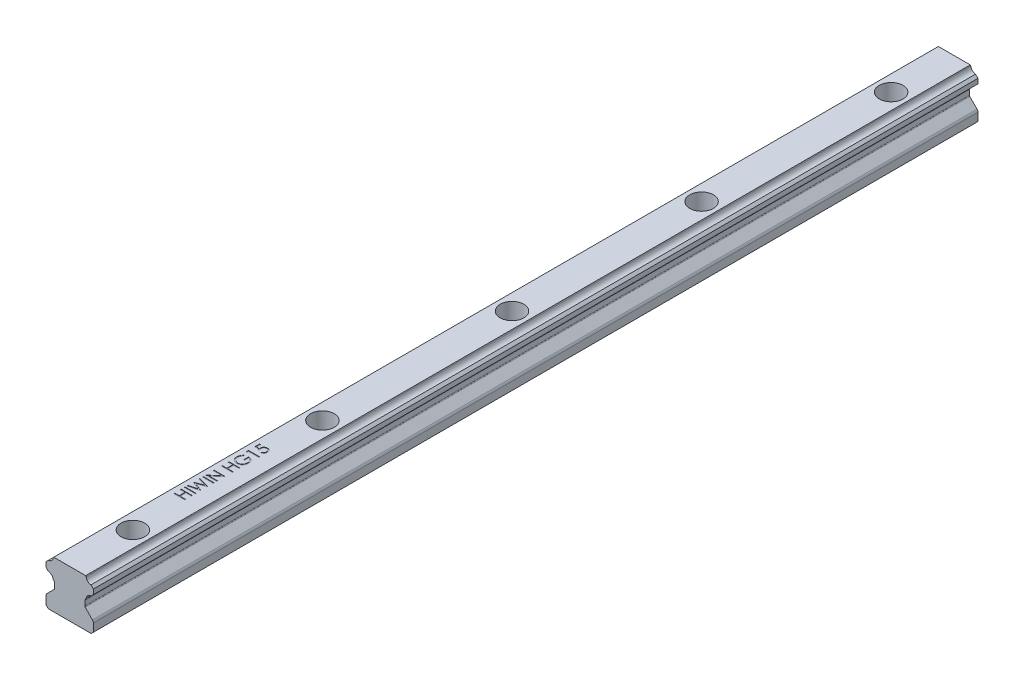
SolidWorks part; units mm, degrees
material "镀铬不锈钢"
ref_plane "前视基准面" through (0, 0, 0) normal (0, 0, 1) x (1, 0, 0)
ref_plane "上视基准面" through (0, 0, 0) normal (0, 1, 0) x (1, 0, 0)
ref_plane "右视基准面" through (0, 0, 0) normal (1, 0, 0) x (0, 0, -1)
sketch "草图1" plane through (0, 0, 0) normal (0, 0, 1) x (1, 0, 0)
  line L20 (7.5, 12.549) -> (6.7304, 13.3186)
  line L21 (-5.049, 15) -> (-5.1049, 14.9441)
  line L22 (-7.5, 12.549) -> (-7.5, 11.011)
  line L23 (6.7419, 10.2529) -> (7.5, 11.011)
  line L24 (-6.7304, 13.3186) -> (-7.5, 12.549)
  line L25 (-4.8872, 6.2704) -> (-7.2071, 3.9505)
  line L26 (-7.5, 0.7) -> (-6.8, 0)
  line L27 (7.2071, 3.9505) -> (4.8872, 6.2704)
  line L28 (-4.77, 8.1153) -> (-4.77, 6.5533)
  line L29 (7.5, 0.7) -> (7.5, 3.2434)
  line L30 (6.8, 0) -> (7.5, 0.7)
  line L31 (-6.8, 0) -> (6.8, 0)
  line L32 (-7.5, 3.2434) -> (-7.5, 0.7)
  line L33 (4.77, 6.5533) -> (4.77, 8.1153)
  line L34 (-5.1032, 8.6142) -> (-4.8872, 8.3982)
  line L35 (5.049, 15) -> (-5.049, 15)
  line L36 (5.1049, 14.9441) -> (5.049, 15)
  line L37 (7.5, 11.011) -> (7.5, 12.549)
  line L38 (4.8872, 8.3982) -> (5.1032, 8.6142)
  line L39 (-7.5, 11.011) -> (-6.7419, 10.2529)
  arc A14 (-5.217, 8.8451) -> (-5.1032, 8.6142) centre (-4.8204, 8.897) ccw
  arc A15 (5.1032, 8.6142) -> (5.217, 8.8451) centre (4.8204, 8.897) ccw
  arc A16 (-5.217, 8.8451) -> (-6.7419, 10.2529) centre (-6.8233, 8.6349) ccw
  arc A17 (-7.2071, 3.9505) -> (-7.5, 3.2434) centre (-6.5, 3.2434) ccw
  arc A18 (4.77, 6.5533) -> (4.8872, 6.2704) centre (5.17, 6.5533) ccw
  arc A19 (-5.1049, 14.9441) -> (-5.2183, 14.7157) centre (-4.822, 14.6613) ccw
  arc A20 (4.8872, 8.3982) -> (4.77, 8.1153) centre (5.17, 8.1153) ccw
  arc A21 (5.2183, 14.7157) -> (5.1049, 14.9441) centre (4.822, 14.6613) ccw
  arc A22 (-6.7304, 13.3186) -> (-5.2183, 14.7157) centre (-6.8233, 14.936) ccw
  arc A23 (6.7419, 10.2529) -> (5.217, 8.8451) centre (6.8233, 8.6349) ccw
  arc A24 (5.2183, 14.7157) -> (6.7304, 13.3186) centre (6.8233, 14.936) ccw
  arc A25 (7.5, 3.2434) -> (7.2071, 3.9505) centre (6.5, 3.2434) ccw
  arc A26 (-4.8872, 6.2704) -> (-4.77, 6.5533) centre (-5.17, 6.5533) ccw
  arc A27 (-4.77, 8.1153) -> (-4.8872, 8.3982) centre (-5.17, 8.1153) ccw
extrude "凸台-拉伸1" add sketch "草图1" against normal blind 280
hole_wizard "M4 六角凹头螺钉的柱形沉头孔1" positions "草图3" profile "草图2" counterbore size "M4" standard "ISO" end condition through all
sketch "草图3" plane through (0.2915, 15, -3.4663) normal (0, 1, 0) x (-1, 0, 0)
  point P0 (0.2915, -16.5337)
  dimension "D1" = 20
sketch "草图2" plane through (0, 15, -20) normal (1, 0, 0) x (0, 0, 1)
  line L0 (0, 0) -> (0, 15)
  line L1 (0, 15) -> (2.25, 15)
  line L3 (2.25, 15) -> (2.25, 5.3)
  line L4 (2.25, 5.3) -> (3.75, 5.3)
  line L5 (3.75, 5.3) -> (3.75, 0)
  line L7 (3.75, 0) -> (0, 0)
  line L11 (0, -6.35) -> (0, 107.95) construction
  dimension "通孔孔直径" = 4.5
  dimension "通孔孔深度" = 15
  dimension "柱形沉头孔直径" = 7.5
  dimension "柱形沉头孔深度" = 5.3
pattern_linear "阵列(线性)1" count 5 spacing 60 along (0, 0, -1) of "M4 六角凹头螺钉的柱形沉头孔1"
sketch "草图6" plane through (0, 15, 0) normal (0, 1, 0) x (1, 0, 0)
  line L0 (0, 20) -> (0, 80) construction
  text T0 "HIWIN HG15"
extrude "切除-拉伸1" cut sketch "草图6" against normal blind 0.1
equation "\"D1@凸台-拉伸1\" = 2 * \"D1@草图3\" + \"D3@阵列(线性)1\" *  ( \"D1@阵列(线性)1\"  - 1) "
